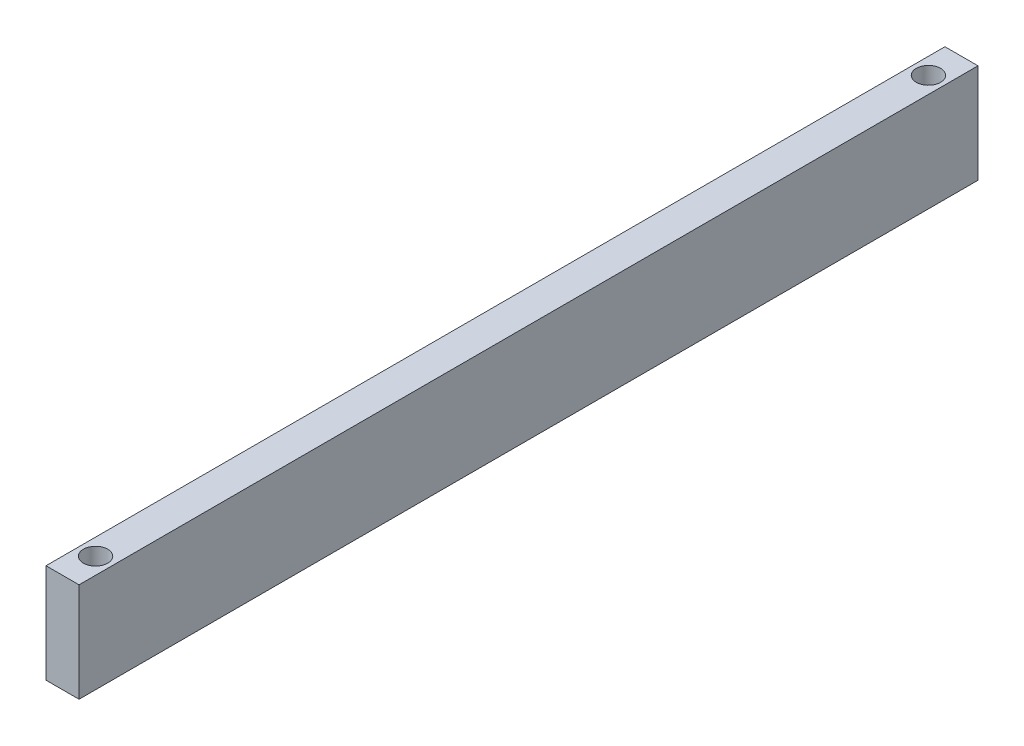
SolidWorks part; units mm, degrees
other "Markup1"
sketch "Sketch6" plane through (0, 0, 0) normal (0.1266, -0.8901, -0.4379) x (-0.2811, -0.4555, 0.8447)
ref_plane "Front Plane" through (0, 0, 0) normal (0, 0, 1) x (1, 0, 0)
ref_plane "Top Plane" through (0, 0, 0) normal (0, 1, 0) x (1, 0, 0)
ref_plane "Right Plane" through (0, 0, 0) normal (1, 0, 0) x (0, 0, -1)
sketch "Sketch1" plane through (0, 0, 0) normal (0, 0, 1) x (1, 0, 0)
  line L0 (0, 0) -> (-6.35, 0)
  line L3 (-6.35, 0) -> (-6.35, 19.05)
  line L4 (-6.35, 19.05) -> (0, 19.05)
  line L5 (0, 19.05) -> (0, 0)
  dimension "D1" = 19.05
  dimension "D4" = 6.35
extrude "Boss-Extrude1" add sketch "Sketch1" along normal blind 172.72
sketch "Sketch2" plane through (0, 19.05, 0) normal (0, 1, 0) x (1, 0, 0)
  line L0 (-3.175, 0) -> (-3.175, -172.72) construction
  line L3 (-6.35, 0) -> (0, 0) construction
  line L4 (-6.35, -172.72) -> (0, -172.72) construction
  circle A0 centre (-3.175, -166.37) radius 2.3368
  circle A1 centre (-3.175, -6.35) radius 2.3368
  dimension "D1" = 4.6736
  dimension "D2" = 6.35
  dimension "D3" = 6.35
sketch "Sketch3" plane through (0, 0, 0) normal (0, -1, 0) x (1, 0, 0)
  line L0 (-3.175, 0) -> (-3.175, 172.72) construction
  line L3 (0, 172.72) -> (0, 0) construction
  line L4 (0, 0) -> (-6.35, 0) construction
  line L5 (0, 172.72) -> (-6.35, 172.72) construction
  circle A0 centre (-3.175, 166.37) radius 2.54
  circle A1 centre (-3.175, 6.35) radius 2.54
  dimension "D2" = 5.08
  dimension "D1" = 3.175
  dimension "D3" = 6.35
  dimension "D4" = 6.35
sketch "Sketch4" plane through (0, 0, 0) normal (1, 0, 0) x (0, 0, -1)
  line L0 (0, 19.05) -> (0, 0) construction
  line L3 (-172.72, 19.05) -> (0, 19.05) construction
  circle A0 centre (-15.24, 12.065) radius 3.175
  dimension "D3" = 6.35
  dimension "D1" = 15.24
  dimension "D2" = 6.985
sketch "Sketch5" plane through (0, 0, 172.72) normal (0, 0, 1) x (1, 0, 0)
  line L1 (-6.35, 0) -> (-12.7, 0)
  line L2 (-6.35, 0) -> (-6.35, 6.35)
  line L3 (-6.35, 6.35) -> (-12.7, 6.35)
  line L4 (-12.7, 0) -> (-12.7, 6.35)
  dimension "D1" = 6.35
  dimension "D2" = 6.35
extrude "Cut-Extrude4" cut sketch "Sketch2" against normal through all
